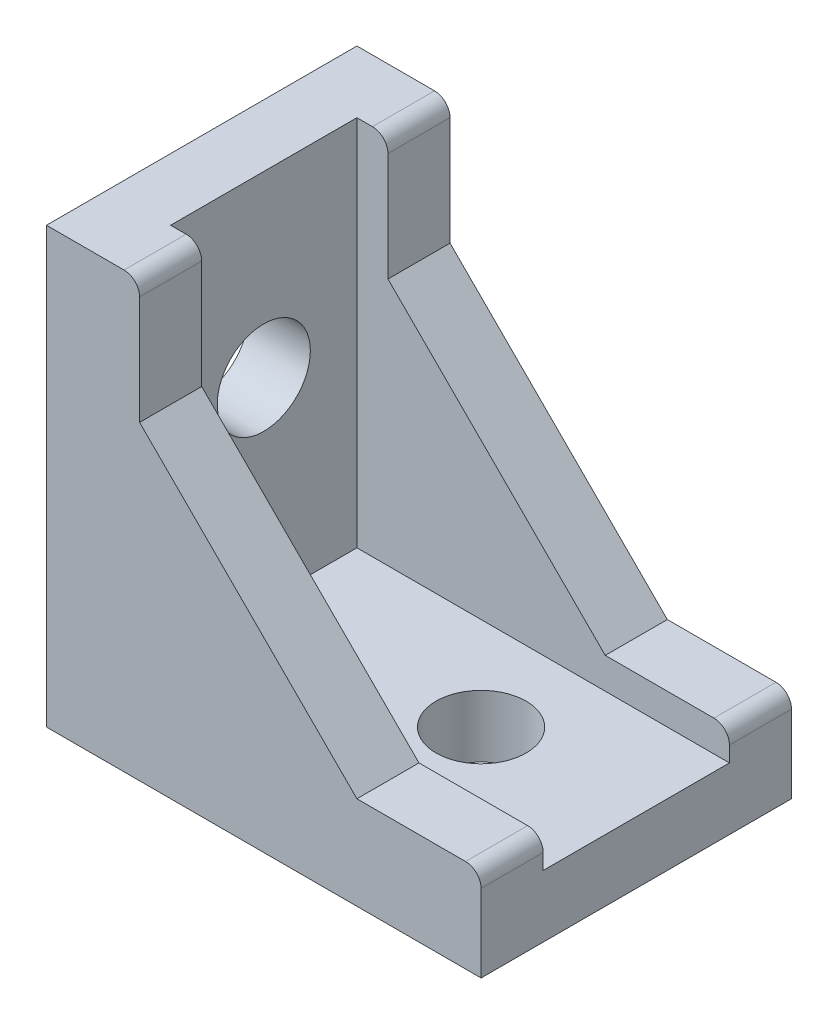
SolidWorks part; units mm, degrees
ref_plane "Front Plane" through (0, 0, 0) normal (0, 0, 1) x (1, 0, 0)
ref_plane "Top Plane" through (0, 0, 0) normal (0, 1, 0) x (1, 0, 0)
ref_plane "Right Plane" through (0, 0, 0) normal (1, 0, 0) x (0, 0, -1)
sketch "Sketch1" plane through (0, 0, 0) normal (0, 0, 1) x (1, 0, 0)
  line L1 (-25.1152, 31.426) -> (-25.1152, 3.426)
  line L2 (-25.1152, 3.426) -> (2.8848, 3.426)
  line L3 (2.8848, 3.426) -> (2.8848, 9.426)
  line L4 (2.8848, 9.426) -> (-5.1152, 9.426)
  line L5 (-5.1152, 9.426) -> (-19.1152, 23.426)
  line L6 (-19.1152, 23.426) -> (-19.1152, 31.426)
  line L7 (-19.1152, 31.426) -> (-25.1152, 31.426)
  dimension "D1" = 28
  dimension "D2" = 28
  dimension "D3" = 6
  dimension "D4" = 6
  dimension "D5" = 8
  dimension "D6" = 8
extrude "Boss-Extrude1" add sketch "Sketch1" along normal blind 20
ref_plane "Plane1" through (0, 0, 10) normal (0, 0, 1) x (1, 0, 0)
sketch "Sketch2" plane through (0, 0, 10) normal (0, 0, 1) x (1, 0, 0)
  line L0 (-25.1152, 3.426) -> (-25.1152, 38.275) construction
  line L4 (-21.1152, 7.426) -> (-21.1152, 38.0167)
  line L5 (-21.1152, 38.0167) -> (15.2713, 38.0167)
  line L6 (15.2713, 38.0167) -> (15.2713, 7.426)
  line L7 (15.2713, 7.426) -> (-21.1152, 7.426)
  line L11 (-25.1152, 3.426) -> (2.8848, 3.426) construction
  dimension "D2" = 4
  dimension "D3" = 4
extrude "Cut-Extrude1" cut sketch "Sketch2" against normal mid plane 12
sketch "Sketch4" plane through (-21.1152, 0, 0) normal (1, 0, 0) x (0, 0, -1)
  line L0 (-10, 35.4387) -> (-10, -2.7611) construction
  line L1 (-10, 15.4) -> (-10, -15.4) construction
  line L2 (-16, 31.426) -> (-4, 31.426) construction
  circle A0 centre (-10, 19.926) radius 3
  dimension "D1" = 6
  dimension "D2" = 11.5
extrude "Cut-Extrude2" cut sketch "Sketch4" against normal blind 12
sketch "Sketch5" plane through (0, 7.426, 0) normal (0, 1, 0) x (1, 0, 0)
  line L0 (-15.4, -10) -> (15.4, -10) construction
  line L1 (2.8848, -4) -> (2.8848, -16) construction
  circle A0 centre (-7.1152, -10) radius 2.9
  dimension "D1" = 5.8
  dimension "D2" = 10
extrude "Cut-Extrude3" cut sketch "Sketch5" against normal blind 12
fillet "Fillet1" radius 1 4 edges at (-19.1152, 31.426, 2) (-19.1152, 31.426, 18) (2.8848, 9.426, 2) (2.8848, 9.426, 18)
